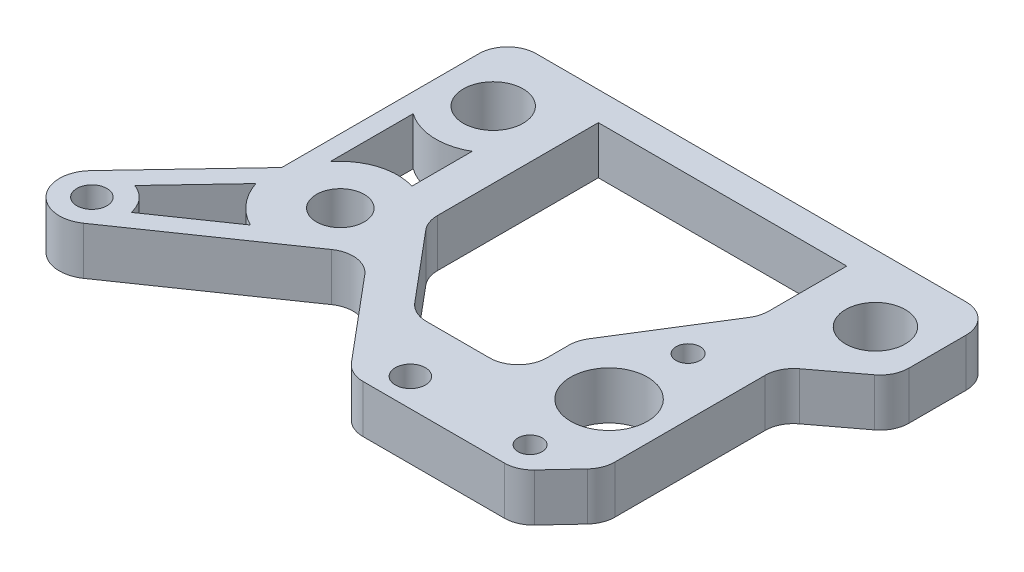
SolidWorks part; units mm, degrees
other "Markup1"
sketch "Sketch6" plane through (-23.3268, 0, -30.7975) normal (-0.0348, 0.9994, -0.0028) x (-0.9993, -0.0348, 0.0153)
material "6061-T6 (SS)"
ref_plane "X-Y Datum" through (0, 0, 0) normal (0, 0, 1) x (1, 0, 0)
ref_plane "X-Z Datum" through (0, 0, 0) normal (0, 1, 0) x (1, 0, 0)
ref_plane "Y-Z Datum" through (0, 0, 0) normal (1, 0, 0) x (0, 0, -1)
other "Graphic1"
other "Graphic (Closed) -1"
other "Graphic (Closed) -2"
sketch "Sketch2" plane through (0, 0, 0) normal (0, 1, 0) x (1, 0, 0)
  line L0 (48.6426, -18.7325) -> (-23.0162, -18.7325)
  line L1 (24.0125, -14.7036) -> (25.7865, -13.7801) construction
  line L2 (0, 0) -> (105.5557, -202.7707) construction
  line L3 (11.142, -21.4036) -> (-3.5026, -29.027) construction
  line L4 (0, 0) -> (0, -121.3797) construction
  line L5 (-3.5026, -29.027) -> (90.9112, -210.3941) construction
  line L6 (90.9112, -210.3941) -> (105.5557, -202.7707) construction
  line L7 (11.142, -21.4036) -> (24.0125, -14.7036) construction
  line L11 (-12.7, 30.7975) -> (57.15, 30.7975)
  line L12 (57.15, 13.0175) -> (57.15, 30.7975)
  line L13 (57.15, 13.0175) -> (-12.7, 13.0175) construction
  line L15 (44.7685, -18.0975) -> (44.7685, -11.3157) construction
  line L16 (44.7685, -18.0975) -> (34.8625, -18.0975) construction
  line L18 (44.7685, 9.8425) -> (34.8625, 9.8425) construction
  line L20 (44.7685, -11.3157) -> (49.8485, -11.3157) construction
  line L21 (49.8485, -11.3157) -> (49.8485, 3.0607) construction
  line L22 (49.8485, 3.0607) -> (44.7685, 3.0607) construction
  line L23 (44.7685, 3.0607) -> (44.7685, 9.8425) construction
  line L24 (34.8625, -18.0975) -> (34.8625, 9.8425) construction
  line L25 (48.6426, -18.7325) -> (57.15, 13.0175)
  line L26 (-12.7, 30.7975) -> (-12.7, 13.0175)
  line L28 (-12.5603, 0) -> (-16.51, -40.5272) construction
  line L30 (-23.0162, -18.7325) -> (-12.7, 13.0175)
  circle A0 centre (0, 0) radius 3.175
  circle A1 centre (24.0125, -14.7036) radius 2
  circle A2 centre (-1.5875, 21.9075) radius 3.9688
  circle A3 centre (49.2125, 21.9075) radius 3.9687
  circle A4 centre (39.8485, -4.1275) radius 5.1
  circle A5 centre (24.0125, -14.7036) radius 3.175 construction
  circle A6 centre (39.8485, -14.6275) radius 1.6
  circle A7 centre (39.8485, 6.3725) radius 1.6
  circle A8 centre (-17.2047, -14.9225) radius 3.175 construction
  circle A9 centre (-17.2047, -14.9225) radius 2
  point P9 (11.142, -21.4036)
  point P30 (49.8485, -4.1275)
  point P31 (34.8625, -4.1275)
  dimension "D1" = 6.35
  dimension "D8" = 4
  dimension "D10" = 7.9375
  dimension "D11" = 7.9375
  dimension "D16" = 27.94
  dimension "D23" = 10.2
  dimension "D20" = 6.35
  dimension "D30" = 3.2
  dimension "D32" = 3.2
  dimension "D34" = 6.35
  dimension "D35" = 4
  dimension "D3" = 13.0175
  dimension "D4" = 16.51
  dimension "D5" = 228.6
  dimension "D6" = 24.13
  dimension "D7" = 27.5
  dimension "D9" = 16.51
  dimension "D12" = 8.89
  dimension "D13" = 69.85
  dimension "D14" = 7.9375
  dimension "D15" = 31.75
  dimension "D17" = 17.78
  dimension "D18" = 3.175
  dimension "D19" = 14.986
  dimension "D21" = 5.08
  dimension "D22" = 14.3764
  dimension "D24" = 10
  dimension "D25" = 36.83
  dimension "D26" = 50.8
  dimension "D27" = 165
  dimension "D28" = 12.7
  dimension "D29" = 17.3015
  dimension "D31" = 10.5
  dimension "D33" = 10.5
  dimension "D36" = 162
extrude "Boss-Extrude1" [suppressed] add sketch "Sketch2" against normal blind 6.35
ref_point "Point1" [suppressed]
sketch "Sketch3" [suppressed] plane through (0, 0, 0) normal (0, 1, 0) x (1, 0, 0)
  line L0 (39.9681, 6.3725) -> (39.9681, -4.1275) construction
  line L1 (57.2697, 12.9663) -> (-12.5803, 12.9663) construction
  line L5 (39.9681, -4.1275) -> (39.9681, -14.6275) construction
  line L6 (42.0297, -18.7325) -> (20.4164, -18.7325)
  line L7 (57.2697, 12.9663) -> (57.2697, 30.7975)
  line L8 (57.2697, 30.7975) -> (-12.5803, 30.7975)
  line L9 (-12.5803, 30.7975) -> (-12.5803, 12.9663)
  line L10 (40.938, 24.6176) -> (16.9472, 10.7666)
  line L11 (13.3942, 11.8528) -> (6.9035, 25.1608)
  line L12 (8.045, 26.9875) -> (40.303, 26.9875)
  line L13 (57.2697, 12.9663) -> (48.3797, 12.9663)
  line L14 (48.3797, 12.9663) -> (48.3797, -12.3825)
  line L16 (-23.0162, -18.7325) -> (48.6426, -18.7325) construction
  line L18 (16.6064, -14.8627) -> (10.2787, -14.8627)
  line L21 (-8.965, -15.5427) -> (-15.106, -18.7325)
  line L24 (-21.1701, -13.6017) -> (-12.5803, 12.9663)
  line L29 (17.8764, -16.1925) -> (17.8764, -16.1327)
  circle A0 centre (0.1197, 0) radius 3.175
  circle A1 centre (-1.4678, 21.9075) radius 3.9688
  circle A2 centre (49.3322, 21.9075) radius 3.9687
  circle A3 centre (39.9681, -4.1275) radius 5.1
  circle A4 centre (39.9681, -14.6275) radius 1.6
  circle A5 centre (39.9681, 6.3725) radius 1.6
  circle A6 centre (24.1322, -14.7036) radius 2
  circle A7 centre (-17.085, -14.9225) radius 2
  arc A8 (13.3942, 11.8528) -> (16.9472, 10.7666) centre (15.6772, 12.9663) ccw
  arc A9 (8.045, 26.9875) -> (6.9035, 25.1608) centre (8.045, 25.7175) ccw
  arc A10 (40.938, 24.6176) -> (40.303, 26.9875) centre (40.303, 25.7175) ccw
  arc A11 (10.2787, -14.8627) -> (-8.965, -15.5427) centre (0.1197, 0) cw
  arc A12 (-15.106, -18.7325) -> (-21.1701, -13.6017) centre (-17.085, -14.9225) cw
  arc A13 (42.0297, -18.7325) -> (48.3797, -12.3825) centre (42.0297, -12.3825) ccw
  arc A14 (20.4164, -18.7325) -> (17.8764, -16.1925) centre (20.4164, -16.1925) cw
  arc A15 (16.6064, -14.8627) -> (17.8764, -16.1327) centre (16.6064, -16.1327) cw
  dimension "D1" = 6.35
  dimension "D4" = 7.9375
  dimension "D9" = 10.2
  dimension "D10" = 3.2
  dimension "D11" = 4
  dimension "D21" = 2.54
  dimension "D22" = 1.27
  dimension "D3" = 6.35
  dimension "D28" = 2.54
  dimension "D29" = 1.27
  dimension "D2" = 7.9375
  dimension "D5" = 50.8
  dimension "D6" = 21.9075
  dimension "D7" = 1.5875
  dimension "D8" = 8.89
  dimension "D12" = 10.5
  dimension "D13" = 17.2047
  dimension "D14" = 24.0125
  dimension "D15" = 14.7036
  dimension "D16" = 39.8485
  dimension "D17" = 4.1275
  dimension "D18" = 14.9225
  dimension "D19" = 69.85
  dimension "D20" = 3.81
  dimension "D23" = 30
  dimension "D24" = 64
  dimension "D25" = 32.258
  dimension "D26" = 15.5575
  dimension "D27" = 25.3488
  dimension "D30" = 8.89
sketch "Sketch4" plane through (0, 0, 0) normal (0, 1, 0) x (1, 0, 0)
  line L0 (39.8485, 6.3725) -> (39.8485, -4.1275) construction
  line L1 (56.1975, 13.0175) -> (-8.5725, 13.0175) construction
  line L2 (39.8485, -4.1275) -> (39.8485, -14.6275) construction
  line L3 (40.2577, -18.4375) -> (21.466, -18.4375)
  line L5 (52.3875, 30.7975) -> (-4.7625, 30.7975)
  line L6 (-8.5725, 26.9875) -> (-8.5725, 0.7817)
  line L7 (40.3225, 26.9875) -> (40.3225, 16.6117)
  line L9 (7.3025, 26.9875) -> (40.3225, 26.9875)
  line L25 (7.3025, 26.9875) -> (7.3025, 5.6144)
  line L26 (8.1939, 3.1653) -> (15.8479, -5.9563)
  line L37 (18.5473, -17.0765) -> (9.2686, -6.0186)
  line L38 (4.1864, -5.3315) -> (-15.328, -18.7942)
  line L40 (47.4685, 8.9851) -> (47.4685, -10.9806)
  line L41 (46.4449, -13.579) -> (43.0442, -17.2259)
  line L42 (27.1485, -7.3173) -> (18.7665, -7.3173)
  line L43 (48.9856, 12.0279) -> (54.6804, 16.3193)
  line L44 (56.1975, 19.3621) -> (56.1975, 26.9875)
  line L45 (39.7436, 14.5927) -> (31.5374, 1.4601)
  line L48 (-8.5725, 0.7817) -> (-20.9174, -12.2732)
  line L49 (30.9585, -3.5073) -> (30.9585, -0.5589)
  line L50 (-17.78, -15.24) -> (0, 0) construction
  line L51 (-13.417, -14.3901) -> (-4.0383, -7.9199)
  line L52 (-16.2728, -11.0583) -> (-8.4443, -2.7795)
  line L55 (2.2225, 7.2887) -> (2.2225, 15.3084)
  line L57 (-6.0325, 4.6555) -> (-6.0325, 15.7183)
  circle A0 centre (0, 0) radius 3.175
  circle A1 centre (-1.5875, 21.9075) radius 3.9688
  circle A2 centre (49.2125, 21.9075) radius 3.9687
  circle A3 centre (39.8485, -4.1275) radius 5.1
  circle A4 centre (39.8485, -14.6275) radius 1.6
  circle A5 centre (39.8485, 6.3725) radius 1.6
  circle A6 centre (24.0125, -14.7036) radius 2
  circle A7 centre (-17.78, -15.24) radius 2
  arc A12 (-15.328, -18.7942) -> (-20.9174, -12.2732) centre (-17.78, -15.24) cw
  arc A19 (-8.5725, 26.9875) -> (-4.7625, 30.7975) centre (-4.7625, 26.9875) cw
  arc A20 (52.3875, 30.7975) -> (56.1975, 26.9875) centre (52.3875, 26.9875) cw
  circle A33 centre (24.0125, -14.7036) radius 3.5 construction
  arc A34 (-4.0383, -7.9199) -> (-8.4443, -2.7795) centre (0, 0) cw
  arc A35 (-13.417, -14.3901) -> (-16.2728, -11.0583) centre (-17.78, -15.24) ccw
  arc A37 (40.3225, 16.6117) -> (39.7436, 14.5927) centre (36.5125, 16.6117) cw
  arc A38 (30.9585, -0.5589) -> (31.5374, 1.4601) centre (34.7685, -0.5589) cw
  arc A39 (27.1485, -7.3173) -> (30.9585, -3.5073) centre (27.1485, -3.5073) ccw
  arc A40 (7.3025, 5.6144) -> (8.1939, 3.1653) centre (11.1125, 5.6144) ccw
  arc A41 (15.8479, -5.9563) -> (18.7665, -7.3173) centre (18.7665, -3.5073) ccw
  arc A42 (9.2686, -6.0186) -> (4.1864, -5.3315) centre (6.35, -8.4676) ccw
  arc A43 (21.466, -18.4375) -> (18.5473, -17.0765) centre (21.466, -14.6275) cw
  arc A45 (56.1975, 19.3621) -> (54.6804, 16.3193) centre (52.3875, 19.3621) cw
  arc A46 (47.4685, 8.9851) -> (48.9856, 12.0279) centre (51.2785, 8.9851) cw
  arc A47 (47.4685, -10.9806) -> (46.4449, -13.579) centre (43.6585, -10.9806) cw
  arc A48 (43.0442, -17.2259) -> (40.2577, -18.4375) centre (40.2577, -14.6275) cw
  arc A49 (2.2225, 15.3084) -> (-6.0325, 15.7183) centre (-1.5875, 21.9075) cw
  arc A50 (2.2225, 7.2887) -> (-6.0325, 4.6555) centre (0, 0) ccw
  point P31 (-14.4051, -12.3472)
  point P38 (-6.7498, -5.7855)
  point P58 (-8.5725, 30.7975)
  point P72 (19.6893, -18.4375)
  point P77 (56.1975, 17.4625)
  point P84 (41.9143, -18.4375)
  dimension "D1" = 6.35
  dimension "D2" = 7.9375
  dimension "D6" = 10.2
  dimension "D7" = 3.2
  dimension "D8" = 4
  dimension "D19" = 4.445
  dimension "D20" = 8.89
  dimension "D25" = 3.81
  dimension "D26" = 7
  dimension "D27" = 22.225
  dimension "D31" = 6
  dimension "D33" = 4.318
  dimension "D37" = 8.89
  dimension "D38" = 2.54
  dimension "D39" = 3.81
  dimension "D48" = 8.382
  dimension "D23" = 3.81
  dimension "D32" = 8.89
  dimension "D46" = 7.62
  dimension "D47" = 7.62
  dimension "D45" = 3.81
  dimension "D3" = 50.8
  dimension "D4" = 21.9075
  dimension "D5" = 1.5875
  dimension "D9" = 10.5
  dimension "D10" = 24.0125
  dimension "D11" = 14.7036
  dimension "D12" = 39.8485
  dimension "D13" = 4.1275
  dimension "D14" = 15.24
  dimension "D15" = 17.78
  dimension "D16" = 6.985
  dimension "D17" = 8.89
  dimension "D18" = 3.81
  dimension "D21" = 17.78
  dimension "D22" = 8.89
  dimension "D24" = 7.62
  dimension "D28" = 130
  dimension "D29" = 5.08
  dimension "D30" = 12
  dimension "D34" = 4.445
  dimension "D35" = 2.54
  dimension "D36" = 9.525
  dimension "D40" = 127
  dimension "D41" = 5.08
  dimension "D42" = 6.35
  dimension "D43" = 137
  dimension "D44" = 148
  dimension "D60" = 6.985
extrude "Boss-Extrude2" add sketch "Sketch4" against normal blind 6.35
ref_point "Point2"
ref_point "Point3"
sketch "Sketch5" plane through (0, 0, 0) normal (0, 1, 0) x (1, 0, 0)
  line L0 (0, 0) -> (0, -33.6075) construction
  line L1 (0, 0) -> (21.4023, -37.0699) construction
  dimension "D1" = 30
ref_point "Point4"
